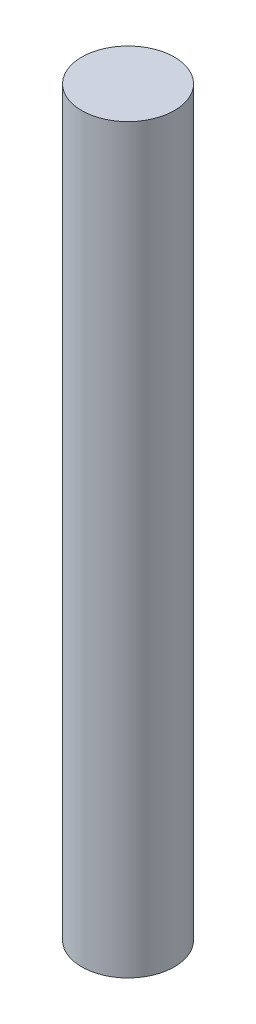
SolidWorks part; units mm, degrees
ref_plane "Front Plane" through (0, 0, 0) normal (0, 0, 1) x (1, 0, 0)
ref_plane "Top Plane" through (0, 0, 0) normal (0, 1, 0) x (1, 0, 0)
ref_plane "Right Plane" through (0, 0, 0) normal (1, 0, 0) x (0, 0, -1)
sketch "Sketch1" plane through (0, 0, 0) normal (0, 1, 0) x (1, 0, 0)
  circle A0 centre (0, 0) radius 9.525
  dimension "D1" = 19.05
extrude "Boss-Extrude1" add sketch "Sketch1" along normal blind 152.4
